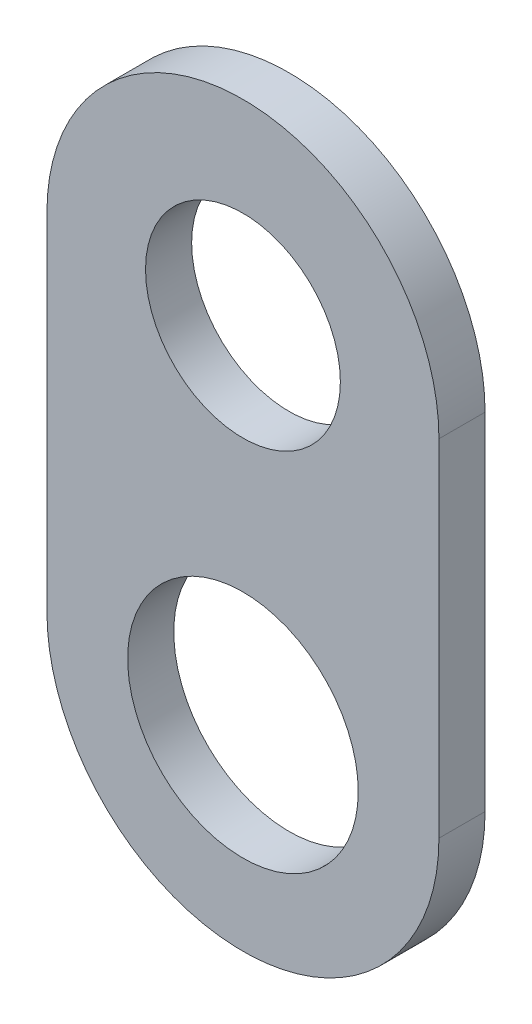
SolidWorks part; units mm, degrees
material "6061-T6 (SS)"
ref_plane "Front Plane" through (0, 0, 0) normal (0, 0, 1) x (1, 0, 0)
ref_plane "Top Plane" through (0, 0, 0) normal (0, 1, 0) x (1, 0, 0)
ref_plane "Right Plane" through (0, 0, 0) normal (1, 0, 0) x (0, 0, -1)
sketch "Sketch1" plane through (0, 0, 0) normal (0, 0, 1) x (1, 0, 0)
  line L0 (0, -38.1) -> (0, 0) construction
  line L1 (-21.59, -38.1) -> (-21.59, 0)
  line L2 (21.59, -38.1) -> (21.59, 0)
  circle A0 centre (0, 0) radius 10.7315
  circle A1 centre (0, -38.1) radius 12.7
  arc A2 (-21.59, -38.1) -> (21.59, -38.1) centre (0, -38.1) ccw
  arc A3 (21.59, 0) -> (-21.59, 0) centre (0, 0) ccw
  point P5 (0, -19.05)
  dimension "D1" = 21.463
  dimension "D2" = 25.4
  dimension "D3" = 8.89
  dimension "D4" = 38.1
extrude "Boss-Extrude1" add sketch "Sketch1" along normal blind 5.08
equation "\"F\"= 500"
equation "\"StressY\"= 40000"
equation "\"SF\"= 4"
equation "\"A\"= ( \"F\" * \"SF\" ) / ( \"StressY\" )"
equation "\"w\"= \"A\" / 0.2"
equation "\"th\"= \"A\" / 0.25"
equation "\"D3@Sketch1\"=.35"
equation "\"D1@Boss-Extrude1\"=\"th\""
